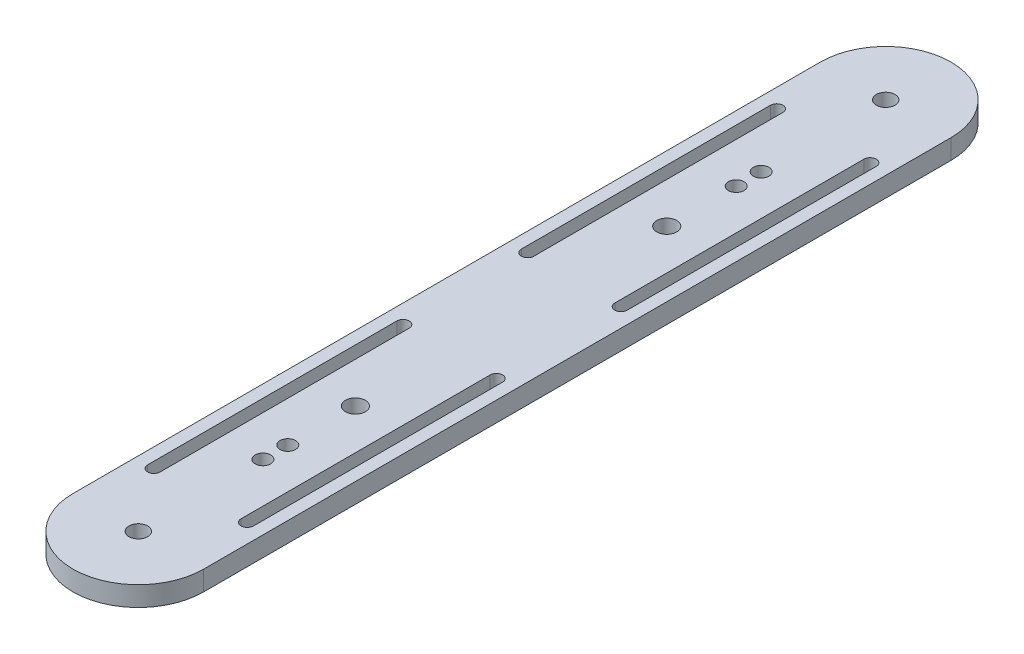
SolidWorks part; units mm, degrees
ref_plane "Front Plane" through (0, 0, 0) normal (0, 0, 1) x (1, 0, 0)
ref_plane "Top Plane" through (0, 0, 0) normal (0, 1, 0) x (1, 0, 0)
ref_plane "Right Plane" through (0, 0, 0) normal (1, 0, 0) x (0, 0, -1)
sketch "Sketch1" plane through (0, 0, 0) normal (0, 1, 0) x (1, 0, 0)
  line L0 (-10.5, 0) -> (-10.5, -120)
  line L1 (10.5, 0) -> (10.5, -120)
  arc A0 (10.5, 0) -> (-10.5, 0) centre (0, 0) ccw
  arc A1 (-10.5, -120) -> (10.5, -120) centre (0, -120) ccw
  circle A2 centre (0, 0) radius 1.5
  circle A5 centre (0, -120) radius 1.5
  dimension "D1" = 10.5
  dimension "D3" = 3
  dimension "D2" = 120
extrude "Boss-Extrude1" add sketch "Sketch1" along normal blind 3.175
sketch "Sketch2" plane through (0, 0, 0) normal (0, -1, 0) x (1, 0, 0)
  arc A0 (0, 18.75) -> (0, 21.25) centre (0, 20) ccw construction
  arc A1 (0, 21.25) -> (0, 18.75) centre (0, 20) ccw construction
  arc A2 (0, 25.25) -> (0, 22.75) centre (0, 24) ccw construction
  arc A3 (0, 22.75) -> (0, 25.25) centre (0, 24) ccw construction
  arc A4 (0, 18.75) -> (0, 21.25) centre (0, 20) ccw
  arc A5 (0, 21.25) -> (0, 18.75) centre (0, 20) ccw
  arc A6 (0, 25.25) -> (0, 22.75) centre (0, 24) ccw
  arc A7 (0, 22.75) -> (0, 25.25) centre (0, 24) ccw
extrude "Cut-Extrude1" cut sketch "Sketch2" against normal through all both and the other way through all
sketch "Sketch3" plane through (0, 3.175, 0) normal (0, 1, 0) x (1, 0, 0)
  arc A0 (0, -97.25) -> (0, -94.75) centre (0, -96) ccw construction
  arc A1 (0, -94.75) -> (0, -97.25) centre (0, -96) ccw construction
  arc A2 (0, -98.75) -> (0, -101.25) centre (0, -100) ccw construction
  arc A3 (0, -101.25) -> (0, -98.75) centre (0, -100) ccw construction
  arc A4 (0, -97.25) -> (0, -94.75) centre (0, -96) ccw
  arc A5 (0, -94.75) -> (0, -97.25) centre (0, -96) ccw
  arc A6 (0, -98.75) -> (0, -101.25) centre (0, -100) ccw
  arc A7 (0, -101.25) -> (0, -98.75) centre (0, -100) ccw
extrude "Cut-Extrude2" cut sketch "Sketch3" against normal through all both and the other way through all
sketch "Sketch4" plane through (0, 3.175, 0) normal (0, 1, 0) x (1, 0, 0)
  circle A0 centre (0, -35.15) radius 1.6 construction
  circle A1 centre (0, -85.15) radius 1.6 construction
  circle A2 centre (0, -35.15) radius 1.6
  circle A3 centre (0, -85.15) radius 1.6
extrude "Cut-Extrude3" cut sketch "Sketch4" against normal through all both and the other way through all
sketch "Sketch5" plane through (0, 0, 0) normal (0, -1, 0) x (1, 0, 0)
  line L0 (0, -10.5) -> (0, 130.5) construction
  line L1 (-10.5, 60) -> (10.5, 60) construction
  line L2 (-10.5, 0) -> (-10.5, 120) construction
  line L3 (10.5, 120) -> (10.5, 0) construction
  line L6 (-8.5, 10) -> (-8.5, 50)
  line L7 (-6.5, 50) -> (-6.5, 10)
  line L8 (6.5, 50) -> (6.5, 10)
  line L9 (8.5, 10) -> (8.5, 50)
  line L22 (8.5, 110) -> (8.5, 70)
  line L23 (6.5, 70) -> (6.5, 110)
  line L24 (-6.5, 70) -> (-6.5, 110)
  line L25 (-8.5, 110) -> (-8.5, 70)
  arc A0 (-10.5, 0) -> (10.5, 0) centre (0, 0) ccw construction
  arc A1 (10.5, 120) -> (-10.5, 120) centre (0, 120) ccw construction
  arc A4 (-8.5, 10) -> (-6.5, 10) centre (-7.5, 10) ccw
  arc A5 (-6.5, 50) -> (-8.5, 50) centre (-7.5, 50) ccw
  arc A6 (6.5, 50) -> (8.5, 50) centre (7.5, 50) cw
  arc A7 (8.5, 10) -> (6.5, 10) centre (7.5, 10) cw
  arc A20 (8.5, 110) -> (6.5, 110) centre (7.5, 110) ccw
  arc A21 (6.5, 70) -> (8.5, 70) centre (7.5, 70) ccw
  arc A22 (-6.5, 70) -> (-8.5, 70) centre (-7.5, 70) cw
  arc A23 (-8.5, 110) -> (-6.5, 110) centre (-7.5, 110) cw
  point P15 (0, 0)
  point P23 (0, 0)
  point P24 (0, 0)
  dimension "D1" = 40
  dimension "D3" = 10
  dimension "D2" = 2
  dimension "D4" = 3
extrude "Cut-Extrude4" cut sketch "Sketch5" against normal blind 40
